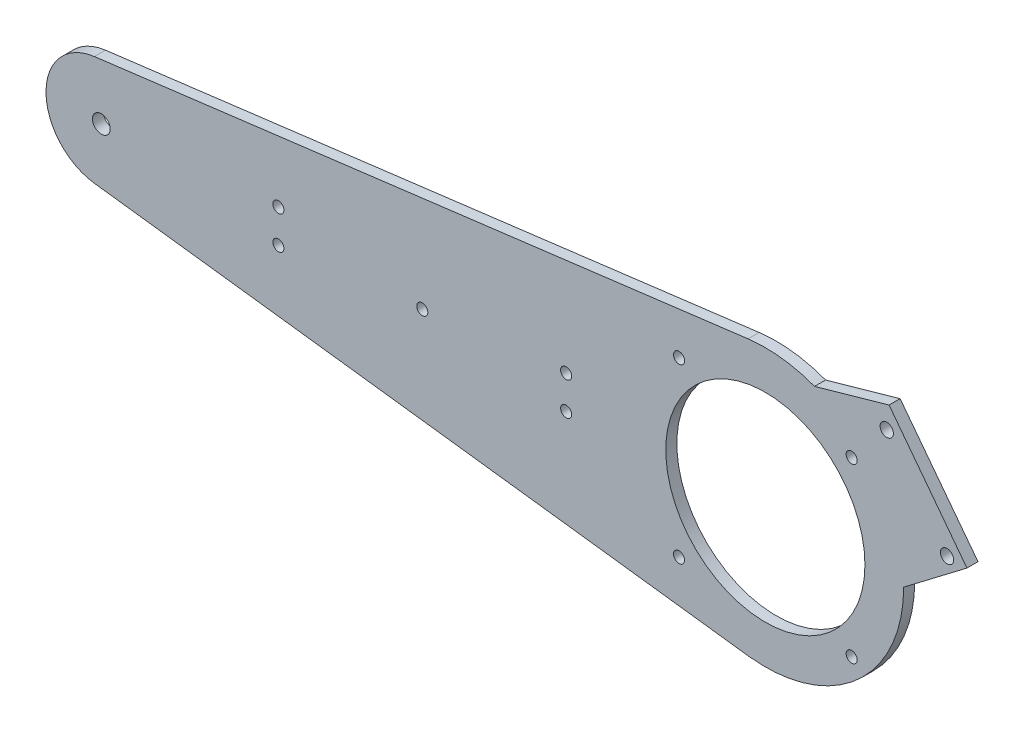
SolidWorks part; units mm, degrees
material "Custom Plastic"
ref_plane "Front Plane" through (0, 0, 0) normal (0, 0, 1) x (1, 0, 0)
ref_plane "Top Plane" through (0, 0, 0) normal (0, 1, 0) x (1, 0, 0)
ref_plane "Right Plane" through (0, 0, 0) normal (1, 0, 0) x (0, 0, -1)
sketch "Sketch1" plane through (0, 0, 0) normal (0, 0, 1) x (1, 0, 0)
  line L0 (39, 39) -> (-39, -39) construction
  line L1 (-39, -39) -> (39, -39) construction
  line L2 (-39, -39) -> (-39, 39) construction
  line L3 (-39, 39) -> (39, 39) construction
  line L4 (39, -39) -> (39, 39) construction
  line L5 (-7.8125, 62.0098) -> (-303.125, 24.8039)
  line L6 (-90, -7.5) -> (-90, 7.5) construction
  line L7 (-303.125, -24.8039) -> (-7.8125, -62.0098)
  line L8 (-90, 7.5) -> (-155, 0) construction
  line L9 (-155, 0) -> (-90, -7.5) construction
  line L10 (-90, -7.5) -> (-3.9902, -22.6512) construction
  line L12 (-90, 7.5) -> (-220, 7.5) construction
  line L13 (-90, 7.5) -> (-90, -7.5) construction
  line L14 (-90, -7.5) -> (-220, -7.5) construction
  line L15 (-220, 7.5) -> (-220, -7.5) construction
  circle A0 centre (0, 0) radius 45
  circle A1 centre (-39, -39) radius 2.5
  circle A3 centre (39, 39) radius 2.5
  circle A4 centre (-39, 39) radius 2.5
  circle A6 centre (39, -39) radius 2.5
  circle A7 centre (0, 0) radius 62.5
  circle A8 centre (-300, 0) radius 4
  circle A9 centre (-300, 0) radius 25
  circle A10 centre (-90, 7.5) radius 2.5
  circle A11 centre (-90, -7.5) radius 2.5
  circle A12 centre (-155, 0) radius 2.5
  circle A13 centre (0, 0) radius 23 construction
  circle A14 centre (-220, 7.5) radius 2.5
  circle A15 centre (-220, -7.5) radius 2.5
  point P7 (0, 0)
  point P26 (-90, 0)
  dimension "D1" = 90
  dimension "D3" = 5
  dimension "D4" = 125
  dimension "D5" = 8
  dimension "D7" = 21
  dimension "D8" = 5
  dimension "D9" = 46
  dimension "D2" = 78
  dimension "D6" = 300
  dimension "D10" = 65
  dimension "D11" = 15
  dimension "D12" = 90
  dimension "D13" = 130
extrude "Boss-Extrude1" add sketch "Sketch1" along normal blind 5 contours A9 L7 A7 L5 | A7 A0 A1 A3 A4 A6 | A9 A8
sketch "Sketch2" plane through (0, 0, 0) normal (0, 0, -1) x (-1, 0, 0)
  line L0 (-62.5, 0) -> (-91.0737, 21.7518)
  line L1 (-91.0737, 21.7518) -> (-55.8899, 67.97)
  line L2 (-55.8899, 67.97) -> (-22.2188, 58.4173)
  line L3 (-22.2188, 58.4173) -> (-51.9487, 34.7502)
  line L4 (-51.9487, 34.7502) -> (-62.5, 0)
  line L7 (-69.6542, 3.0411) -> (-89.5463, 18.184) construction
  line L8 (-55.8899, 67.97) -> (-92.2328, 20.2291) construction
  line L9 (-54.2763, 66.7417) -> (-34.8001, 51.9153) construction
  circle A0 centre (-54.8408, 57.7455) radius 3
  circle A1 centre (-82.098, 21.9398) radius 3
  circle A2 centre (-54.8408, 57.7455) radius 3 construction
  circle A3 centre (-82.098, 21.9398) radius 3 construction
  arc A4 (7.8125, 62.0098) -> (7.8125, -62.0098) centre (0, 0) ccw construction
  point P18 (-92.6942, 21.9127)
  point P19 (-62.5, 0)
  point P20 (-97.3028, 25.2573)
  point P23 (0, 0)
  point P26 (-53.2381, 32.7408)
  point P27 (0, 0)
  dimension "D1" = 35
  dimension "D2" = 38
extrude "Boss-Extrude3" add sketch "Sketch2" against normal up to surface (5 mm away) up to face at (-217.5, -7.5, 5)
